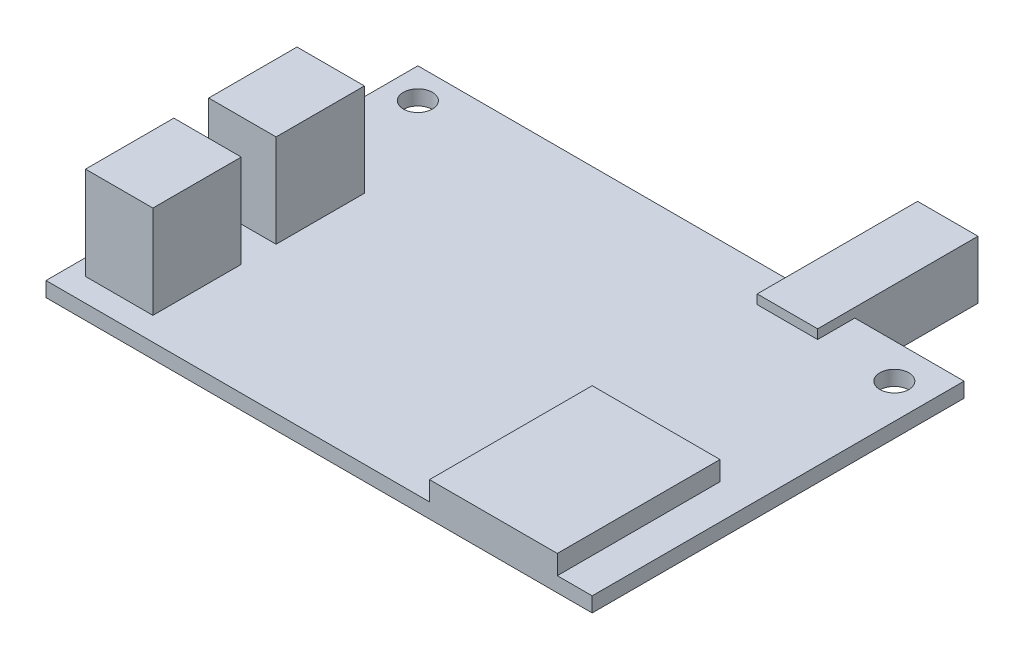
SolidWorks part; units mm, degrees
material "PBT General Purpose"
ref_plane "Front Plane" through (0, 0, 0) normal (0, 0, 1) x (1, 0, 0)
ref_plane "Top Plane" through (0, 0, 0) normal (0, 1, 0) x (1, 0, 0)
ref_plane "Right Plane" through (0, 0, 0) normal (1, 0, 0) x (0, 0, -1)
sketch "Sketch1" plane through (0, 0, 0) normal (0, 1, 0) x (1, 0, 0)
  line L1 (-29.845, -20.32) -> (29.845, -20.32)
  line L2 (-29.845, -20.32) -> (-29.845, 20.32)
  line L3 (-29.845, 20.32) -> (29.845, 20.32)
  line L4 (29.845, -20.32) -> (29.845, 20.32)
  line L5 (-29.845, -20.32) -> (29.845, 20.32) construction
  line L6 (-29.845, 20.32) -> (29.845, -20.32) construction
  circle A0 centre (26.035, 16.51) radius 1.5875
  circle A1 centre (-26.543, 17.018) radius 1.5875
  point P0 (0, 0)
  dimension "D3" = 3.175
  dimension "D1" = 59.69
  dimension "D2" = 40.64
  dimension "D4" = 55.88
  dimension "D5" = 36.83
  dimension "D6" = 37.338
  dimension "D7" = 3.302
extrude "Boss-Extrude1" add sketch "Sketch1" along normal blind 1.6256
sketch "Sketch2" plane through (0, 1.6256, 0) normal (0, 1, 0) x (1, 0, 0)
  line L0 (-29.845, -20.32) -> (29.845, -20.32) construction
  line L1 (26.035, -20.32) -> (12.065, -20.32)
  line L2 (26.035, -20.32) -> (26.035, -2.54)
  line L3 (26.035, -2.54) -> (12.065, -2.54)
  line L4 (12.065, -20.32) -> (12.065, -2.54)
  line L5 (29.845, -20.32) -> (29.845, 20.32) construction
  dimension "D1" = 13.97
  dimension "D2" = 17.78
  dimension "D3" = 3.81
extrude "Boss-Extrude2" add sketch "Sketch2" along normal blind 2.1082
sketch "Sketch3" plane through (0, 1.6256, 0) normal (0, 1, 0) x (1, 0, 0)
  line L0 (29.845, -20.32) -> (29.845, 20.32) construction
  line L1 (17.907, 16.256) -> (11.303, 16.256)
  line L2 (17.907, 16.256) -> (17.907, 33.782)
  line L3 (17.907, 33.782) -> (11.303, 33.782)
  line L4 (11.303, 16.256) -> (11.303, 33.782)
  line L5 (29.845, 20.32) -> (-29.845, 20.32) construction
  dimension "D1" = 11.938
  dimension "D2" = 6.604
  dimension "D3" = 4.064
  dimension "D4" = 13.462
extrude "Boss-Extrude3" add sketch "Sketch3" against normal blind 6.35 from offset 1.016
sketch "Sketch4" plane through (0, 1.6256, 0) normal (0, 1, 0) x (1, 0, 0)
  line L1 (-28.067, -17.78) -> (-20.701, -17.78)
  line L2 (-28.067, -17.78) -> (-28.067, -8.128)
  line L3 (-28.067, -8.128) -> (-20.701, -8.128)
  line L4 (-20.701, -17.78) -> (-20.701, -8.128)
  line L6 (-28.067, -4.318) -> (-20.701, -4.318)
  line L7 (-28.067, -4.318) -> (-28.067, 5.334)
  line L8 (-28.067, 5.334) -> (-20.701, 5.334)
  line L9 (-20.701, -4.318) -> (-20.701, 5.334)
  line L10 (-29.845, 20.32) -> (-29.845, -20.32) construction
  line L11 (-29.845, -20.32) -> (12.065, -20.32) construction
  dimension "D1" = 9.652
  dimension "D2" = 9.652
  dimension "D3" = 7.366
  dimension "D4" = 1.778
  dimension "D5" = 2.54
  dimension "D6" = 3.81
extrude "Boss-Extrude4" add sketch "Sketch4" along normal blind 10.16
equation "\"D2@Sketch4\"=\"D1@Sketch4\""
